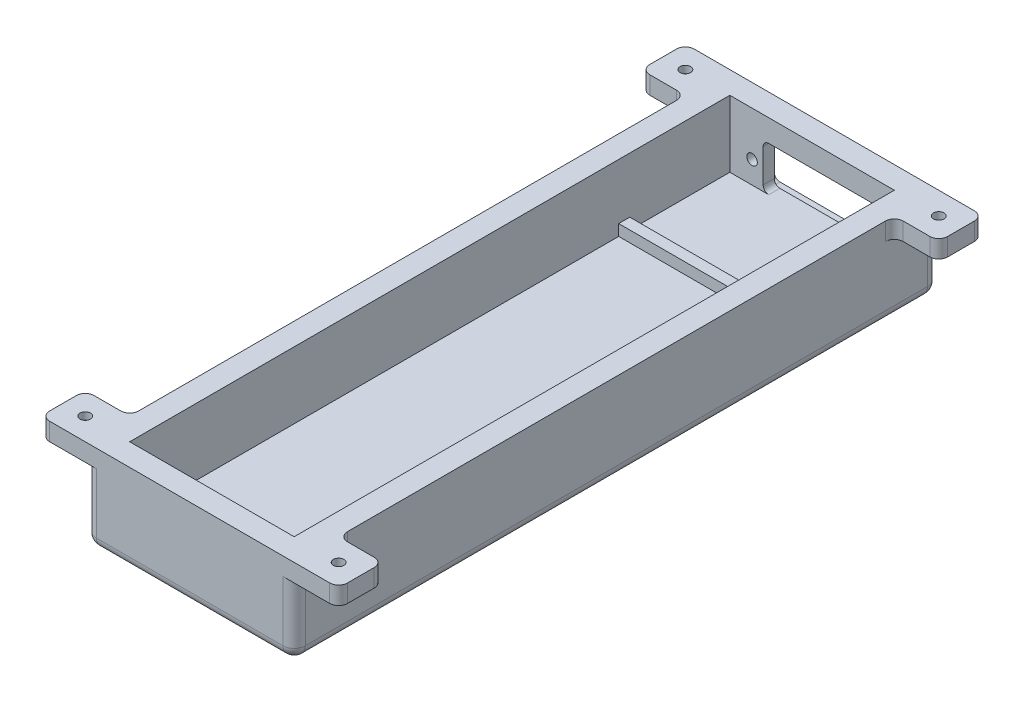
SolidWorks part; units mm, degrees
ref_plane "Front Plane" through (0, 0, 0) normal (0, 0, 1) x (1, 0, 0)
ref_plane "Top Plane" through (0, 0, 0) normal (0, 1, 0) x (1, 0, 0)
ref_plane "Right Plane" through (0, 0, 0) normal (1, 0, 0) x (0, 0, -1)
sketch "Sketch1" plane through (0, 0, 0) normal (0, 1, 0) x (1, 0, 0)
  line L0 (-23.495, 69.85) -> (-23.495, 107.95)
  line L1 (-23.495, -69.85) -> (23.495, -69.85)
  line L2 (-23.495, -69.85) -> (-23.495, 69.85)
  line L3 (-23.495, 69.85) -> (23.495, 69.85)
  line L4 (23.495, -69.85) -> (23.495, 69.85)
  line L5 (-23.495, -69.85) -> (23.495, 69.85) construction
  line L6 (-23.495, 69.85) -> (23.495, -69.85) construction
  line L7 (-23.495, 107.95) -> (23.495, 107.95)
  line L8 (23.495, 107.95) -> (23.495, 69.85)
  line L9 (-29.845, -76.2) -> (29.845, -76.2)
  line L10 (29.845, -76.2) -> (29.845, 107.95)
  line L11 (29.845, 107.95) -> (23.495, 107.95)
  line L12 (-23.495, 107.95) -> (-29.845, 107.95)
  line L13 (-29.845, 107.95) -> (-29.845, -76.2)
  point P0 (0, 0)
  dimension "D1" = 46.99
  dimension "D2" = 139.7
  dimension "D3" = 38.1
  dimension "D4" = 6.35
  dimension "D5" = 6.35
  dimension "D6" = 6.35
extrude "Boss-Extrude1" add sketch "Sketch1" along normal blind 25.4
shell "Shell1" thickness 6.35
sketch "Sketch2" plane through (0, 6.35, 0) normal (0, 1, 0) x (1, 0, 0)
  line L0 (-23.495, 73.025) -> (23.495, 73.025)
  line L1 (-23.495, 69.85) -> (-23.495, 107.95) construction
  line L2 (23.495, 107.95) -> (23.495, 69.85) construction
  line L3 (23.495, 73.025) -> (23.495, 69.85)
  line L5 (-23.495, 69.85) -> (-23.495, 73.025)
  line L7 (23.495, 69.85) -> (-23.495, 69.85)
  dimension "D1" = 3.175
extrude "Boss-Extrude2" add sketch "Sketch2" along normal blind 3.175
sketch "Sketch3" plane through (0, 25.4, 0) normal (0, 1, 0) x (1, 0, 0)
  line L1 (-29.845, 107.95) -> (-42.545, 107.95)
  line L2 (-29.845, 107.95) -> (-29.845, 95.25)
  line L3 (-29.845, 95.25) -> (-42.545, 95.25)
  line L4 (-42.545, 107.95) -> (-42.545, 95.25)
  line L5 (0, -13.97) -> (0, 13.97) construction
  line L6 (-29.845, -76.2) -> (-42.545, -76.2)
  line L7 (-29.845, -76.2) -> (-29.845, -63.5)
  line L8 (-29.845, -63.5) -> (-42.545, -63.5)
  line L9 (-42.545, -76.2) -> (-42.545, -63.5)
  line L10 (42.545, -76.2) -> (42.545, -63.5)
  line L11 (29.845, -76.2) -> (42.545, -76.2)
  line L12 (29.845, -76.2) -> (29.845, -63.5)
  line L13 (29.845, -63.5) -> (42.545, -63.5)
  line L14 (29.845, 107.95) -> (29.845, 95.25)
  line L15 (29.845, 95.25) -> (42.545, 95.25)
  line L16 (42.545, 107.95) -> (42.545, 95.25)
  line L17 (29.845, 107.95) -> (42.545, 107.95)
  dimension "D1" = 12.7
  dimension "D2" = 12.7
  dimension "D3" = 12.7
  dimension "D4" = 12.7
extrude "Boss-Extrude3" add sketch "Sketch3" against normal blind 5.08
fillet "Fillet1" radius 2.54 12 edges at (29.845, 22.86, 63.5) (42.545, 22.86, 63.5) (42.545, 22.86, 76.2) (-42.545, 22.86, 76.2) (-42.545, 22.86, 63.5) (-29.845, 22.86, 63.5) (-29.845, 22.86, -95.25) (29.845, 22.86, -95.25) (42.545, 22.86, -95.25) (42.545, 22.86, -107.95) (-42.545, 22.86, -107.95) (-42.545, 22.86, -95.25)
hole_wizard "CBORE for #00 Binding Head Machine Screw1" positions "Sketch6" profile "Sketch7" counterbore size "#00" standard "ANSI Inch" end condition through all
sketch "Sketch6" plane through (0, 20.32, 0) normal (0, -1, 0) x (-1, 0, 0)
  line L0 (-42.545, 97.79) -> (-42.545, 105.41) construction
  line L1 (-40.005, 107.95) -> (-29.845, 107.95) construction
  line L2 (-29.845, -76.2) -> (-40.005, -76.2) construction
  line L3 (42.545, -66.04) -> (42.545, -73.66) construction
  point P0 (-36.195, -69.85)
  point P2 (36.195, -69.85)
  point P4 (36.195, 101.6)
  point P6 (-36.195, 101.6)
  dimension "D1" = 6.35
  dimension "D2" = 6.35
  dimension "D3" = 6.35
  dimension "D4" = 6.35
sketch "Sketch7" plane through (36.195, 20.32, 69.85) normal (1, 0, 0) x (0, 0, -1)
  line L0 (0, 0) -> (0, 5.08)
  line L1 (0, 5.08) -> (1.5, 5.08)
  line L3 (1.5, 5.08) -> (1.5, 3)
  line L4 (1.5, 3) -> (3, 3)
  line L5 (3, 3) -> (3, 0)
  line L7 (3, 0) -> (0, 0)
  line L11 (0, -6.35) -> (0, 107.95) construction
  dimension "Thru Hole Dia." = 3
  dimension "Thru Hole Depth" = 5.08
  dimension "C'Bore Dia." = 6
  dimension "C'Bore Depth" = 3
sketch "Sketch8" plane through (0, 0, -107.95) normal (0, 0, -1) x (-1, 0, 0)
  line L0 (29.845, 20.32) -> (29.845, 0) construction
  line L1 (-20.32, 20.6375) -> (17.145, 20.6375)
  line L2 (-20.32, 20.6375) -> (-20.32, 4.7625)
  line L3 (-20.32, 4.7625) -> (17.145, 4.7625)
  line L4 (17.145, 20.6375) -> (17.145, 4.7625)
  line L5 (23.495, 0) -> (-23.495, 0) construction
  line L6 (-29.845, 20.32) -> (-29.845, 0) construction
  line L7 (-40.005, 25.4) -> (40.005, 25.4) construction
  line L8 (17.145, 20.6375) -> (17.145, 17.4625)
  line L9 (17.145, 4.7625) -> (17.145, 7.9375)
  arc A0 (17.145, 17.4625) -> (17.145, 7.9375) centre (17.145, 12.7) cw
  dimension "D1" = 4.7625
  dimension "D2" = 9.525
  dimension "D3" = 12.7
  dimension "D4" = 4.7625
  dimension "D5" = 3.175
  dimension "D6" = 3.175
extrude "Cut-Extrude1" cut sketch "Sketch8" against normal offset from surface (3.175 mm away) 3.175 contours A0 L4 | L4 L1 L2 L3
sketch "Sketch9" plane through (0, 0, -104.775) normal (0, 0, -1) x (-1, 0, 0)
  line L0 (17.145, 20.6375) -> (-20.32, 20.6375) construction
  line L1 (13.97, 6.35) -> (-18.7325, 6.35)
  line L2 (13.97, 6.35) -> (13.97, 19.05)
  line L3 (13.97, 19.05) -> (-18.7325, 19.05)
  line L4 (-18.7325, 6.35) -> (-18.7325, 19.05)
  line L5 (-20.32, 20.6375) -> (-20.32, 4.7625) construction
  line L6 (-20.32, 4.7625) -> (17.145, 4.7625) construction
  line L7 (17.145, 4.7625) -> (17.145, 7.9375) construction
  circle A0 centre (17.145, 12.7) radius 1.5
  dimension "D5" = 3
  dimension "D1" = 1.5875
  dimension "D2" = 1.5875
  dimension "D3" = 1.5875
  dimension "D4" = 3.175
extrude "Cut-Extrude2" cut sketch "Sketch9" against normal up to next
fillet "Fillet2" radius 1.5875 8 edges at (-17.145, 4.7625, -106.3625) (-13.97, 6.35, -103.1875) (-13.97, 19.05, -103.1875) (-17.145, 20.6375, -106.3625) (20.32, 4.7625, -106.3625) (18.7325, 6.35, -103.1875) (18.7325, 19.05, -103.1875) (20.32, 20.6375, -106.3625)
sketch "Sketch10" plane through (0, 0, -101.6) normal (0, 0, 1) x (1, 0, 0)
  line L0 (18.7325, 17.4625) -> (18.7325, 7.9375) construction
  line L1 (18.7325, 15.0812) -> (23.495, 15.0812)
  line L2 (18.7325, 15.0812) -> (18.7325, 10.3187)
  line L3 (18.7325, 10.3187) -> (23.495, 10.3187)
  line L4 (23.495, 15.0812) -> (23.495, 10.3187)
  line L5 (20.32, 19.05) -> (20.32, 6.35) construction
  point P8 (20.32, 12.7)
  point P9 (18.7325, 12.7)
  dimension "D1" = 4.7625
  dimension "D2" = 4.7625
extrude "Cut-Extrude3" cut sketch "Sketch10" against normal offset from surface (4.7625 mm away) 1.5875 up to face at (0, 16.51, -107.95)
fillet "Fillet4" radius 3.175 8 edges at (0, 0, 76.2) (-29.845, 0, -15.875) (0, 0, -107.95) (29.845, 0, -15.875) (29.845, 10.16, 76.2) (-29.845, 10.16, 76.2) (29.845, 10.16, -107.95) (-29.845, 10.16, -107.95)
